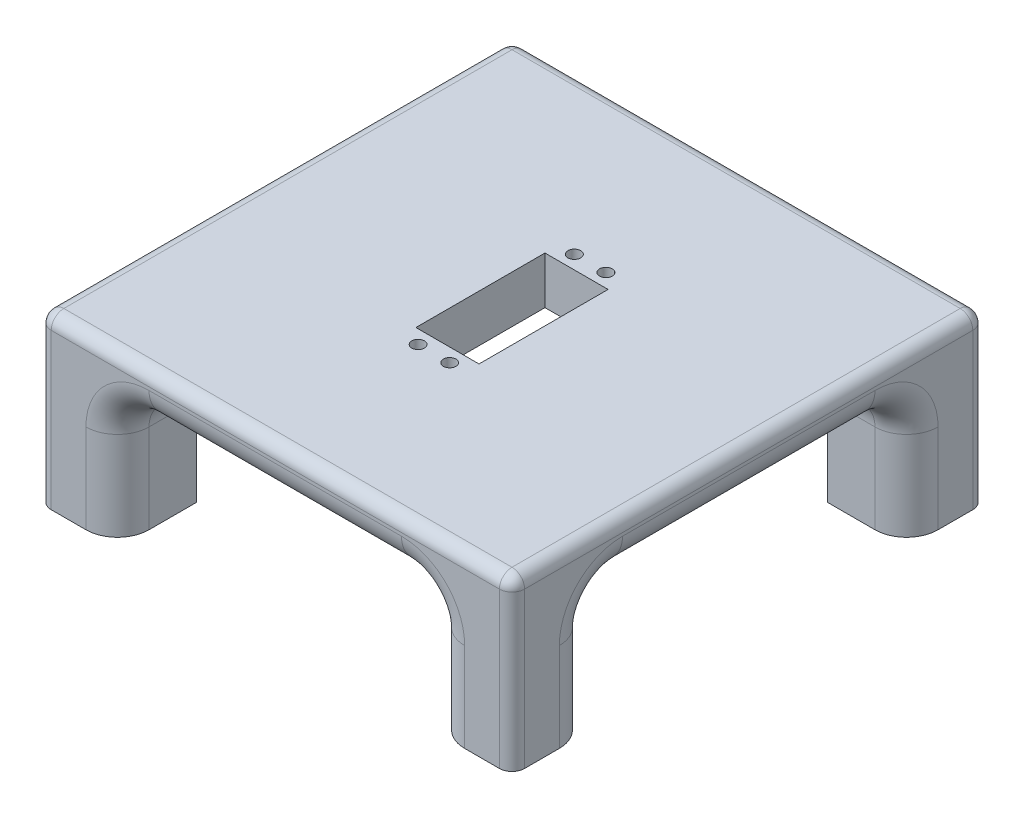
SolidWorks part; units mm, degrees
ref_plane "Front Plane" through (0, 0, 0) normal (0, 0, 1) x (1, 0, 0)
ref_plane "Top Plane" through (0, 0, 0) normal (0, 1, 0) x (1, 0, 0)
ref_plane "Right Plane" through (0, 0, 0) normal (1, 0, 0) x (0, 0, -1)
sketch "Sketch1" plane through (0, 0, 0) normal (0, 1, 0) x (1, 0, 0)
  line L1 (0, 0) -> (-150, 0)
  line L2 (0, 0) -> (0, 150)
  line L3 (0, 150) -> (-150, 150)
  line L4 (-150, 0) -> (-150, 150)
  dimension "D1" = 150
  dimension "D2" = 150
extrude "Boss-Extrude1" add sketch "Sketch1" along normal blind 15
sketch "Sketch2" plane through (0, 15, 0) normal (0, 1, 0) x (1, 0, 0)
  line L0 (-150, 150) -> (0, 0) construction
  line L1 (0, 0) -> (0, 150) construction
  line L2 (0, 150) -> (-150, 0) construction
  line L3 (-85, 75) -> (-65, 75) construction
  line L4 (-65, 54.553) -> (-85, 54.553)
  line L5 (-65, 54.553) -> (-65, 95.447)
  line L6 (-65, 95.447) -> (-85, 95.447)
  line L7 (-85, 54.553) -> (-85, 95.447)
  line L8 (-75, 95.447) -> (-75, 54.553) construction
  point P16 (-75, 75)
  dimension "D1" = 20
  dimension "D2" = 40.894
extrude "Cut-Extrude1" cut sketch "Sketch2" against normal up to surface (15 mm away) up to face at (-75, 0, -75)
sketch "Sketch4" plane through (0, 0, 0) normal (0, -1, 0) x (1, 0, 0)
  line L0 (-75, 0) -> (-75, -150) construction
  line L1 (-150, 0) -> (-125, 0)
  line L2 (-150, 0) -> (-150, -25)
  line L3 (-150, -25) -> (-125, -25)
  line L4 (-125, 0) -> (-125, -25)
  line L5 (-150, 0) -> (0, 0) construction
  line L6 (0, -150) -> (-150, -150) construction
  line L7 (-75, -75) -> (-150, -75) construction
  line L8 (-150, -150) -> (-150, 0) construction
  line L9 (-150, -75) -> (0, -75) construction
  line L10 (0, 0) -> (0, -150) construction
  line L11 (-125, -150) -> (-125, -125)
  line L12 (-150, -125) -> (-125, -125)
  line L13 (-150, -150) -> (-150, -125)
  line L14 (-150, -150) -> (-125, -150)
  line L15 (-25, 0) -> (-25, -25)
  line L16 (0, -25) -> (-25, -25)
  line L17 (0, 0) -> (0, -25)
  line L18 (0, 0) -> (-25, 0)
  line L19 (0, -150) -> (-25, -150)
  line L20 (0, -150) -> (0, -125)
  line L21 (0, -125) -> (-25, -125)
  line L22 (-25, -150) -> (-25, -125)
  dimension "D1" = 25
  dimension "D2" = 25
extrude "Boss-Extrude2" add sketch "Sketch4" along normal blind 38.222
fillet "Fillet1" radius 10 20 edges at (-125, -19.111, 0) (-25, -19.111, 0) (0, -19.111, -25) (0, -19.111, -125) (-25, -19.111, -150) (-125, -19.111, -150) (-150, -19.111, -125) (-150, -19.111, -25) (-75, 0, 0) (0, 0, -75) (-75, 0, -150) (-150, 0, -75) (-25, 0, -12.5) (-12.5, 0, -25) (-12.5, 0, -125) (-25, 0, -137.5) (-125, 0, -137.5) (-137.5, 0, -125) (-137.5, 0, -25) (-125, 0, -12.5)
fillet "Fillet2" radius 4 8 edges at (-75, 15, -150) (-150, -11.611, -150) (-150, 15, -75) (-75, 15, 0) (0, 15, -75) (0, -11.611, -150) (0, -11.611, 0) (-150, -11.611, 0)
sketch "Sketch5" plane through (0, 15, 0) normal (0, 1, 0) x (1, 0, 0)
  circle A1 centre (-80, 50.25) radius 2
  circle A2 centre (-80, 50.25) radius 2
  circle A3 centre (-70, 50.25) radius 2
  circle A4 centre (-70, 50.25) radius 2
  circle A5 centre (-80, 99.75) radius 2.01
  circle A6 centre (-80, 99.75) radius 2.01
  circle A7 centre (-70, 99.75) radius 2.01
  circle A8 centre (-70, 99.75) radius 2.01
  dimension "D1" = 0
  dimension "D2" = 0
  dimension "D3" = 0
  dimension "D4" = 0
extrude "Cut-Extrude2" cut sketch "Sketch5" against normal up to surface (53.222 mm away) up to face at (-11.1674, -38.222, -11.1674)
